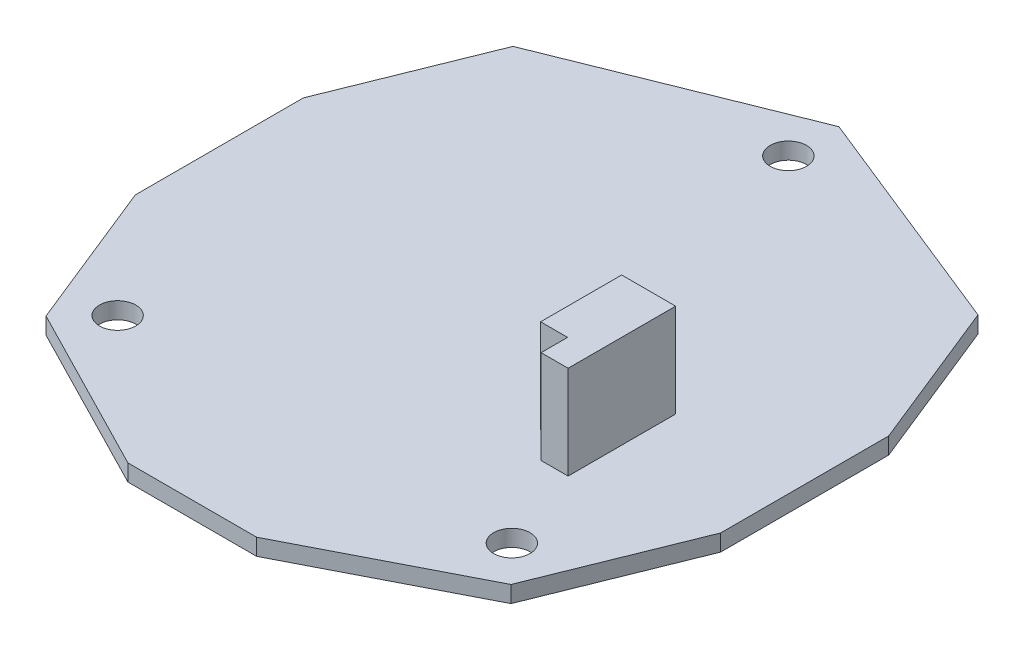
SolidWorks part; units mm, degrees
ref_plane "Front Plane" through (0, 0, 0) normal (0, 0, 1) x (1, 0, 0)
ref_plane "Top Plane" through (0, 0, 0) normal (0, 1, 0) x (1, 0, 0)
ref_plane "Right Plane" through (0, 0, 0) normal (1, 0, 0) x (0, 0, -1)
sketch "Sketch1" plane through (0, 0, 0) normal (0, 1, 0) x (1, 0, 0)
  line L0 (-28.2, 22.15) -> (28.2, 22.15) construction
  line L1 (-28.2, 31.15) -> (28.2, 31.15) construction
  line L2 (-28.2, 31.15) -> (-28.2, -31.15) construction
  line L3 (-28.2, -31.15) -> (28.2, -31.15) construction
  line L4 (28.2, 31.15) -> (28.2, -31.15) construction
  line L5 (-28.2, 31.15) -> (28.2, -31.15) construction
  line L6 (-28.2, -31.15) -> (28.2, 31.15) construction
  line L7 (-28.2, 7.75) -> (28.2, 7.75) construction
  line L8 (-28.2, -8.44) -> (28.2, -8.44) construction
  line L9 (-28.2, -22.84) -> (28.2, -22.84) construction
  line L10 (0, 31.15) -> (22.4, 22.15)
  line L11 (22.4, 22.15) -> (28.2, 7.75)
  line L12 (28.2, 7.75) -> (28.2, -8.44)
  line L13 (28.2, -8.44) -> (22.4, -22.84)
  line L14 (22.4, -22.84) -> (6.2, -31.15)
  line L15 (6.2, -31.15) -> (-6.2, -31.15)
  line L16 (-6.2, -31.15) -> (-22.4, -22.84)
  line L17 (-22.4, -22.84) -> (-28.2, -8.44)
  line L18 (-28.2, -8.44) -> (-28.2, 7.75)
  line L19 (-28.2, 7.75) -> (-22.4, 22.15)
  line L20 (-22.4, 22.15) -> (0, 31.15)
  point P0 (0, 0)
  point P8 (22.4, 22.15)
  point P9 (0, 31.15)
  point P16 (-22.4, 22.15)
  point P17 (-22.4, -22.84)
  point P18 (22.4, -22.84)
  point P19 (6.2, -31.15)
  point P20 (-6.2, -31.15)
  dimension "D1" = 56.4
  dimension "D2" = 62.3
  dimension "D3" = 9
  dimension "D4" = 5.8
  dimension "D5" = 14.4
  dimension "D6" = 16.19
  dimension "D7" = 14.4
  dimension "D8" = 5.8
  dimension "D9" = 5.8
  dimension "D10" = 5.8
  dimension "D11" = 22
  dimension "D12" = 22
extrude "Boss-Extrude1" add sketch "Sketch1" along normal blind 1.6
sketch "Sketch2" plane through (0, 1.6, 0) normal (0, 1, 0) x (1, 0, 0)
  line L0 (0, 31.15) -> (0, -31.15) construction
  line L1 (-6.2, -31.15) -> (6.2, -31.15) construction
  line L2 (28.2, -8.44) -> (28.2, -31.15) construction
  line L3 (28.2, -31.15) -> (0, -31.15) construction
  circle A0 centre (0, 26.28) radius 1.75
  circle A1 centre (18.99, -19.35) radius 1.75
  circle A2 centre (-18.99, -19.35) radius 1.75
  dimension "D2" = 3.5
  dimension "D5" = 3.5
  dimension "D1" = 4.87
  dimension "D3" = 9.21
  dimension "D4" = 11.8
extrude "Cut-Extrude1" cut sketch "Sketch2" against normal blind 1.6
sketch "Sketch3" plane through (0, 1.6, 0) normal (0, 1, 0) x (1, 0, 0)
  line L0 (28.2, -8.44) -> (28.2, -31.15) construction
  line L1 (6.2, -31.15) -> (28.2, -31.15) construction
  line L2 (13.51, -8.5) -> (13.51, -11.05)
  line L3 (16.11, -11.05) -> (13.51, -11.05)
  line L4 (16.11, -11.05) -> (16.11, -0.69)
  line L5 (16.11, -0.69) -> (13.51, -0.69)
  line L7 (13.51, -0.69) -> (10.91, -0.69)
  line L9 (13.51, -8.5) -> (10.91, -8.5)
  line L10 (10.91, -0.69) -> (10.91, -8.5)
  dimension "D1" = 12.09
  dimension "D2" = 20.1
  dimension "D3" = 2.6
  dimension "D4" = 10.36
  dimension "D5" = 2.6
  dimension "D6" = 7.81
extrude "Boss-Extrude2" add sketch "Sketch3" along normal blind 9
